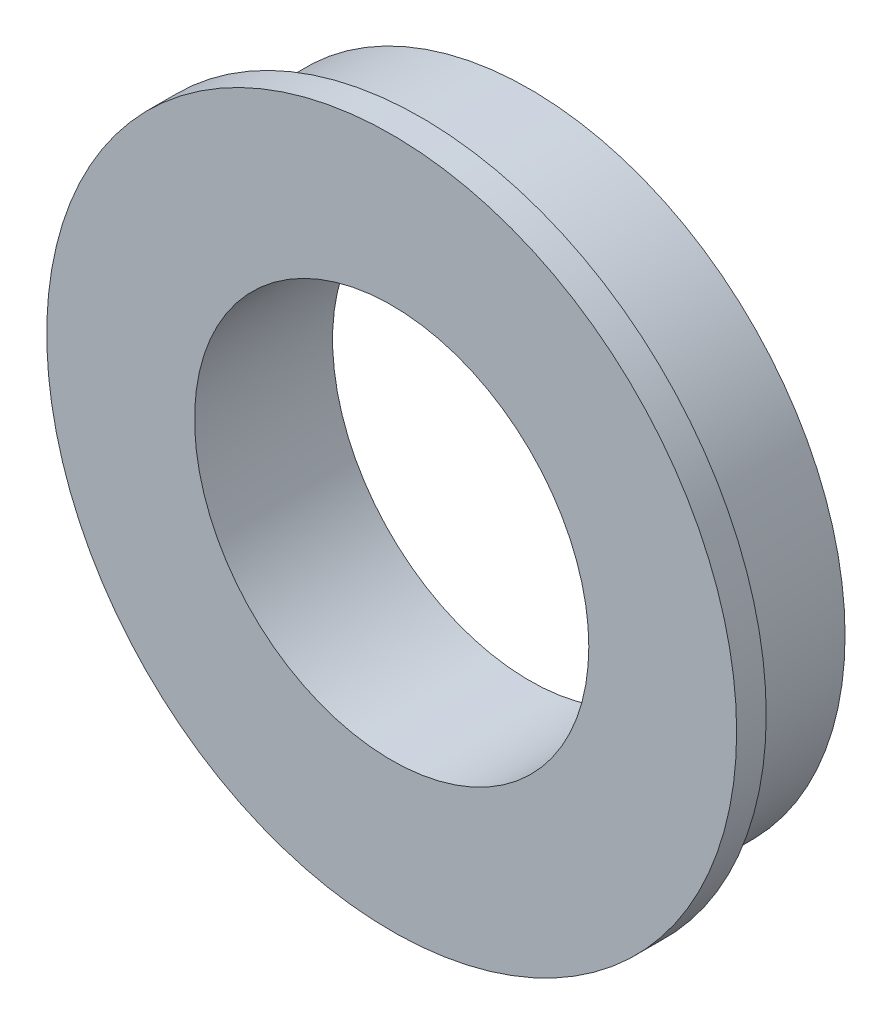
SolidWorks part; units mm, degrees
ref_plane "前视基准面" through (0, 0, 0) normal (0, 0, 1) x (1, 0, 0)
ref_plane "上视基准面" through (0, 0, 0) normal (0, 1, 0) x (1, 0, 0)
ref_plane "右视基准面" through (0, 0, 0) normal (1, 0, 0) x (0, 0, -1)
sketch "草图1" plane through (0, 0, 0) normal (0, 0, 1) x (1, 0, 0)
  circle A0 centre (0, 0) radius 10
  circle A1 centre (0, 0) radius 16
  dimension "D1" = 20
  dimension "D2" = 32
extrude "凸台-拉伸1" add sketch "草图1" along normal blind 5.5
sketch "草图2" plane through (0, 0, 5.5) normal (0, 0, 1) x (1, 0, 0)
  circle A0 centre (0, 0) radius 10
  circle A1 centre (0, 0) radius 17.5
  dimension "D1" = 20
  dimension "D2" = 35
extrude "凸台-拉伸2" add sketch "草图2" along normal blind 1.5
